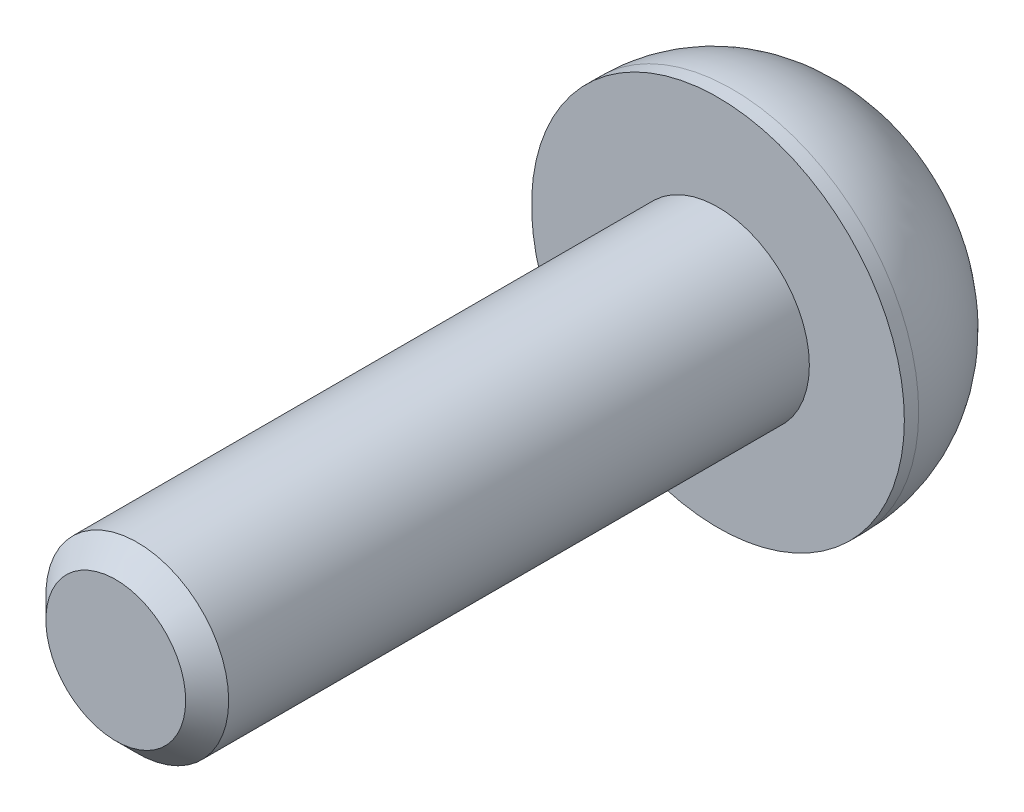
SolidWorks part; units mm, degrees
ref_plane "Přední rovina" through (0, 0, 0) normal (0, 0, 1) x (1, 0, 0)
ref_plane "Horní rovina" through (0, 0, 0) normal (0, 1, 0) x (1, 0, 0)
ref_plane "Pravá rovina" through (0, 0, 0) normal (1, 0, 0) x (0, 0, -1)
sketch "Skica1" plane through (0, 0, 0) normal (0, 0, 1) x (1, 0, 0)
  circle A0 centre (0, 0) radius 2.6
  dimension "D2" = 5.2
extrude "Přidat vysunutím1" add sketch "Skica1" along normal blind 2.2
sketch "Skica2" plane through (0, 0, 2.2) normal (0, 0, 1) x (1, 0, 0)
  circle A0 centre (0, 0) radius 1.275
  dimension "D1" = 2.55
extrude "Přidat vysunutím2" add sketch "Skica2" along normal blind 8.4
fillet "Zaoblit1" radius 2 1 edges at (2.6, 0, 0)
sketch "Skica3" plane through (0, 0, 0) normal (0, 0, -1) x (-1, 0, 0)
  line L0 (0, 3.2614) -> (0, -3.6026) construction
  line L1 (-3.5241, 0) -> (3.8993, 0) construction
  line L2 (-1.65, 0) -> (-1.65, 0.25)
  line L3 (-1.65, 0.25) -> (-0.25, 0.25)
  line L4 (-0.25, 0.25) -> (-0.25, 1.65)
  line L5 (-0.25, 1.65) -> (0.25, 1.65)
  line L6 (0.25, 1.65) -> (0.25, 0.25)
  line L7 (0.25, 0.25) -> (1.65, 0.25)
  line L8 (1.65, 0.25) -> (1.65, -0.25)
  line L9 (0.25, -1.65) -> (0.25, -0.25)
  line L10 (0.25, -0.25) -> (1.65, -0.25)
  line L11 (0.25, -1.65) -> (-0.25, -1.65)
  line L12 (-0.25, -1.65) -> (-0.25, -0.25)
  line L13 (-0.25, -0.25) -> (-1.65, -0.25)
  line L14 (-1.65, -0.25) -> (-1.65, 0)
  dimension "D1" = 0.5
  dimension "D2" = 0.5
  dimension "D3" = 0.5
  dimension "D4" = 0.5
  dimension "D5" = 1.4
  dimension "D6" = 1.4
  dimension "D7" = 1.4
  dimension "D8" = 1.4
extrude "Odebrat vysunutím1" cut sketch "Skica3" against normal blind 0.7
chamfer "Zkosení1" distance 0.3 angle 45 1 edges at (1.275, 0, 10.6)
